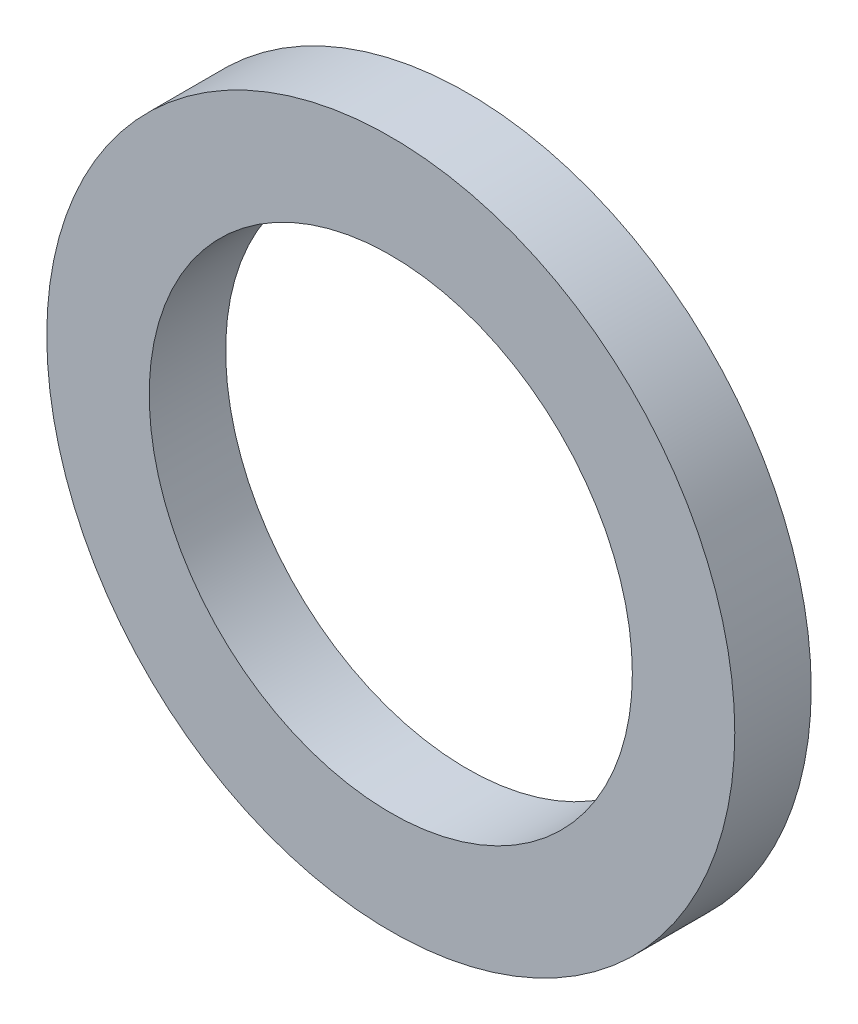
SolidWorks part; units mm, degrees
material "Nylon 101"
ref_plane "Front Plane" through (0, 0, 0) normal (0, 0, 1) x (1, 0, 0)
ref_plane "Top Plane" through (0, 0, 0) normal (0, 1, 0) x (1, 0, 0)
ref_plane "Right Plane" through (0, 0, 0) normal (1, 0, 0) x (0, 0, -1)
sketch "Sketch1" plane through (0, 0, 0) normal (0, 0, 1) x (1, 0, 0)
  circle A0 centre (0, 0) radius 7.1438
  circle A1 centre (0, 0) radius 5.0165
  dimension "D1" = 10.033
  dimension "D2" = 14.2875
extrude "Boss-Extrude1" add sketch "Sketch1" along normal blind 1.5875
